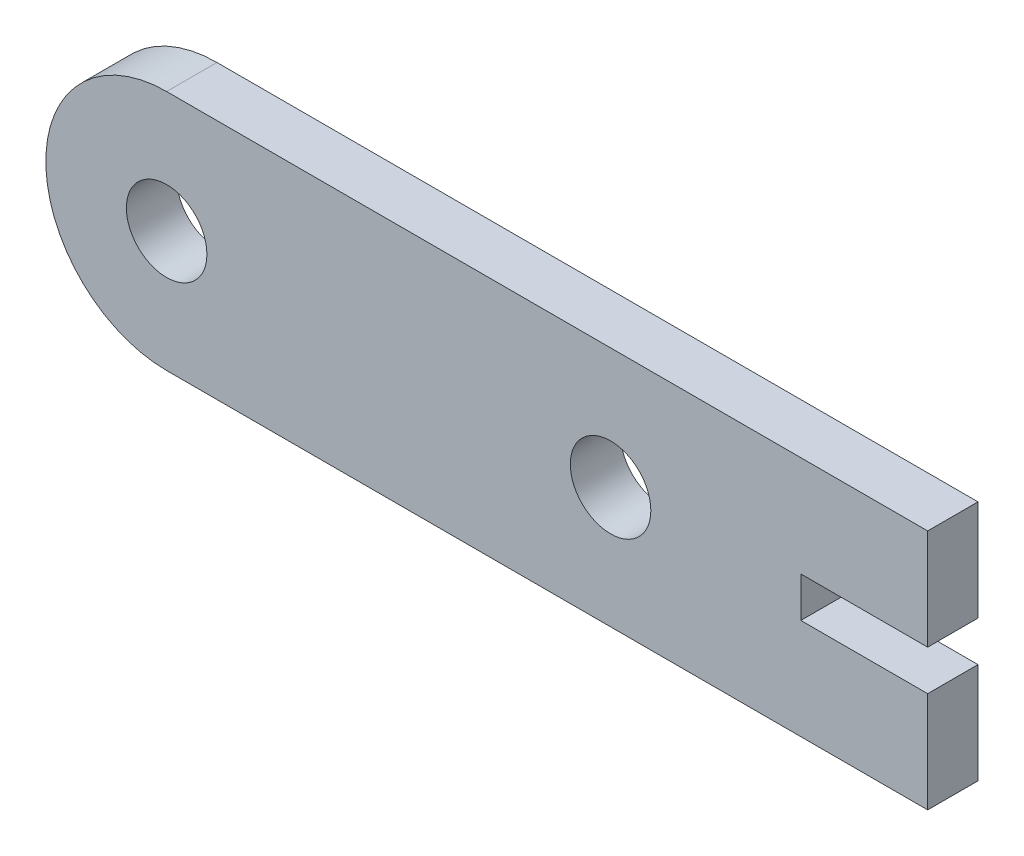
SolidWorks part; units mm, degrees
ref_plane "Front Plane" through (0, 0, 0) normal (0, 0, 1) x (1, 0, 0)
ref_plane "Top Plane" through (0, 0, 0) normal (0, 1, 0) x (1, 0, 0)
ref_plane "Right Plane" through (0, 0, 0) normal (1, 0, 0) x (0, 0, -1)
sketch "Sketch1" plane through (0, 0, 0) normal (0, 0, 1) x (1, 0, 0)
  line L0 (0, 0) -> (70, 0) construction
  line L1 (0, 19.05) -> (120, 19.05)
  line L2 (120, 19.05) -> (120, 3.175)
  line L3 (120, -19.05) -> (0, -19.05)
  line L5 (120, 3.175) -> (100, 3.175)
  line L6 (100, 3.175) -> (100, -3.175)
  line L7 (100, -3.175) -> (120, -3.175)
  line L8 (100, 0) -> (120, 0) construction
  line L9 (120, -3.175) -> (120, -19.05)
  line L10 (120, 3.175) -> (120, 0) construction
  line L11 (120, 0) -> (120, -3.175) construction
  circle A0 centre (0, 0) radius 6.35
  arc A1 (0, 19.05) -> (0, -19.05) centre (0, 0) ccw
  circle A2 centre (70, 0) radius 6.35
  point P16 (0, 0)
  dimension "D2" = 12.7
  dimension "D3" = 38.1
  dimension "D1" = 70
  dimension "D4" = 50
  dimension "D7" = 6.35
  dimension "D8" = 20
extrude "Boss-Extrude1" add sketch "Sketch1" along normal blind 7.9375
